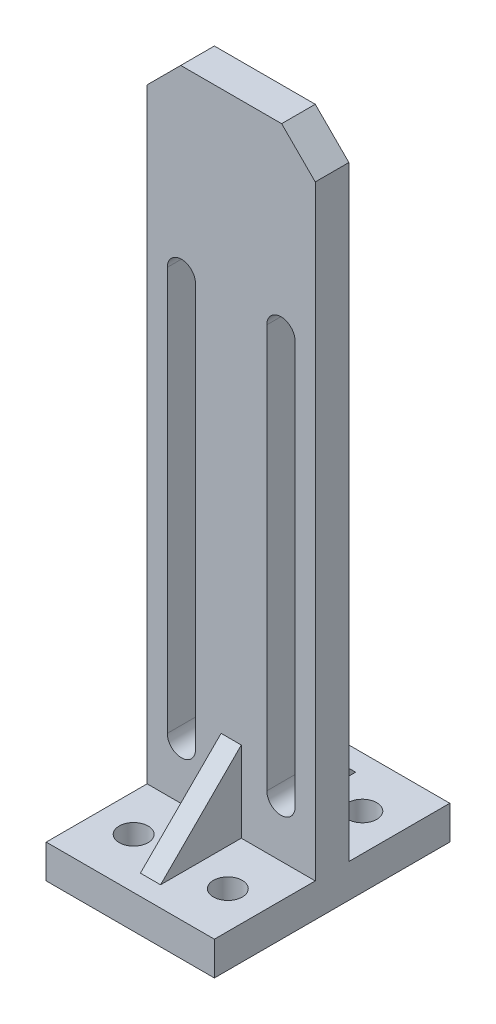
SolidWorks part; units mm, degrees
ref_plane "Front Plane" through (0, 0, 0) normal (0, 0, 1) x (1, 0, 0)
ref_plane "Top Plane" through (0, 0, 0) normal (0, 1, 0) x (1, 0, 0)
ref_plane "Right Plane" through (0, 0, 0) normal (1, 0, 0) x (0, 0, -1)
sketch "Sketch1" plane through (0, 0, 0) normal (0, 0, 1) x (1, 0, 0)
  line L0 (-12.5, 45) -> (-7.5, 50)
  line L1 (-7.5, 50) -> (7.5, 50)
  line L2 (-12.5, 45) -> (-12.5, -50)
  line L3 (-12.5, -50) -> (12.5, -50)
  line L4 (12.5, 45) -> (12.5, -50)
  line L5 (-12.5, 50) -> (12.5, -50) construction
  line L6 (-12.5, -50) -> (12.5, 50) construction
  line L7 (7.5, 50) -> (12.5, 45)
  line L8 (0, 0) -> (0, 50) construction
  line L9 (7.4, -50) -> (7.4, 55.1134) construction
  line L10 (7.4, 23) -> (7.4, -37) construction
  line L11 (9.5, 23) -> (9.5, -37)
  line L12 (5.3, 23) -> (5.3, -37)
  line L13 (-7.4, 23) -> (-7.4, -37) construction
  line L14 (-9.5, 23) -> (-9.5, -37)
  line L15 (-5.3, 23) -> (-5.3, -37)
  arc A0 (9.5, 23) -> (5.3, 23) centre (7.4, 23) ccw
  arc A1 (5.3, -37) -> (9.5, -37) centre (7.4, -37) ccw
  arc A2 (-9.5, 23) -> (-5.3, 23) centre (-7.4, 23) cw
  arc A3 (-5.3, -37) -> (-9.5, -37) centre (-7.4, -37) cw
  point P0 (0, 0)
  point P14 (7.4, -7)
  point P23 (-7.4, -7)
  dimension "D1" = 100
  dimension "D2" = 25
  dimension "D3" = 4.2
  dimension "D4" = 3
  dimension "D7" = 13
  dimension "D8" = 60
extrude "Boss-Extrude1" add sketch "Sketch1" along normal mid plane 5
sketch "Sketch2" plane through (0, 0, 0) normal (1, 0, 0) x (0, 0, -1)
  line L0 (0, 0) -> (0, -10.5504) construction
  line L1 (2.5, -45) -> (17.5, -45)
  line L2 (-2.5, -50) -> (-17.5, -50)
  line L3 (-2.5, -50) -> (-2.5, -45)
  line L4 (-2.5, -45) -> (-17.5, -45)
  line L5 (-17.5, -50) -> (-17.5, -45)
  line L6 (17.5, -50) -> (17.5, -45)
  line L7 (2.5, -50) -> (17.5, -50)
  line L8 (2.5, -50) -> (2.5, -45)
  dimension "D1" = 5
  dimension "D2" = 15
extrude "Boss-Extrude2" add sketch "Sketch2" along normal mid plane 25
sketch "Sketch5" plane through (0, 0, 0) normal (1, 0, 0) x (0, 0, -1)
  line L0 (-14.5, -45) -> (-2.5, -33)
  line L1 (-2.5, -45) -> (-17.5, -45) construction
  line L2 (-2.5, -45) -> (-2.5, 45) construction
  line L3 (-2.5, -33) -> (-2.5, -45)
  line L4 (-2.5, -45) -> (-14.5, -45)
  line L5 (0, 0) -> (0, -7.4969) construction
  line L6 (2.5, -33) -> (2.5, -45)
  line L7 (14.5, -45) -> (2.5, -33)
  line L8 (2.5, -45) -> (14.5, -45)
  dimension "D1" = 12
  dimension "D2" = 12
extrude "Boss-Extrude3" add sketch "Sketch5" along normal mid plane 3
sketch "Sketch6" plane through (0, -45, 0) normal (0, 1, 0) x (1, 0, 0)
  line L0 (-12.5, 17.5) -> (-1.5, 2.5) construction
  line L1 (1.5, 2.5) -> (12.5, 17.5) construction
  line L2 (0, 0) -> (5.3744, 0) construction
  line L3 (0, 0) -> (0, 5.0167) construction
  circle A0 centre (-7, 10) radius 2.15
  circle A1 centre (7, 10) radius 2.15
  circle A2 centre (7, -10) radius 2.15
  circle A3 centre (-7, -10) radius 2.15
  dimension "D1" = 4.3
extrude "Cut-Extrude1" cut sketch "Sketch6" against normal up to surface (5 mm away) up to face at (0, -50, 0)
